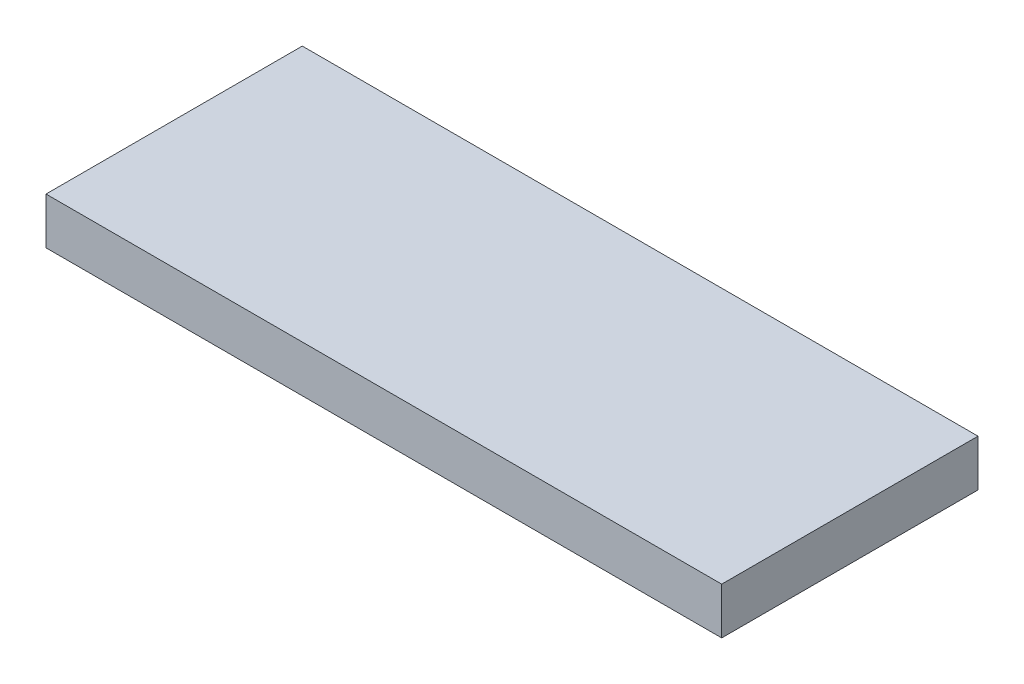
SolidWorks part; units mm, degrees
material "PVC Rigid"
ref_plane "Frontal Plane" through (0, 0, 0) normal (0, 0, 1) x (1, 0, 0)
ref_plane "Horizontal Plane" through (0, 0, 0) normal (0, 1, 0) x (1, 0, 0)
ref_plane "Profile Plane" through (0, 0, 0) normal (1, 0, 0) x (0, 0, -1)
sketch "Sketch1" plane through (0, 0, 0) normal (0, 1, 0) x (1, 0, 0)
  line L1 (-184.15, 69.85) -> (184.15, 69.85)
  line L2 (-184.15, 69.85) -> (-184.15, -69.85)
  line L3 (-184.15, -69.85) -> (184.15, -69.85)
  line L4 (184.15, 69.85) -> (184.15, -69.85)
  line L5 (-184.15, 69.85) -> (184.15, -69.85) construction
  line L6 (-184.15, -69.85) -> (184.15, 69.85) construction
  point P0 (0, 0)
  dimension "D1" = 139.7
  dimension "D2" = 368.3
extrude "Boss-Extrude1" add sketch "Sketch1" along normal blind 25.4
